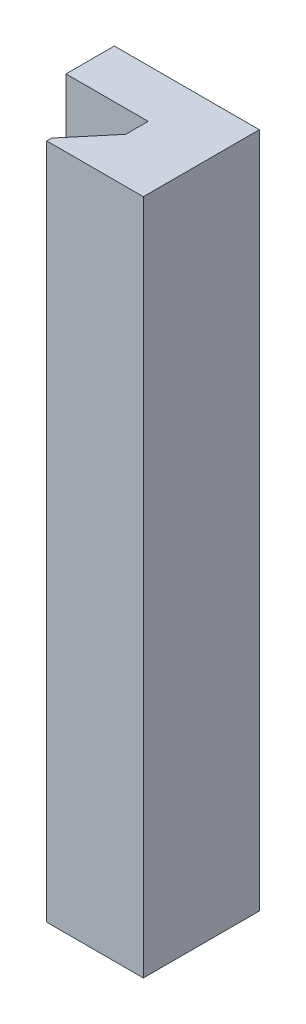
SolidWorks part; units mm, degrees
ref_plane "前视基准面" through (0, 0, 0) normal (0, 0, 1) x (1, 0, 0)
ref_plane "上视基准面" through (0, 0, 0) normal (0, 1, 0) x (1, 0, 0)
ref_plane "右视基准面" through (0, 0, 0) normal (1, 0, 0) x (0, 0, -1)
other "Configuration Table"
sketch "草图1" plane through (0, 0, 0) normal (0, 0, 1) x (1, 0, 0)
  line L1 (0, 0) -> (35, 0)
  line L2 (0, 0) -> (0, -70)
  line L3 (0, -70) -> (35, -70)
  line L4 (35, 0) -> (35, -70)
  dimension "D1" = 70
  dimension "D2" = 35
extrude "凸台-拉伸1" add sketch "草图1" along normal blind 12
sketch "草图2" plane through (0, -70, 0) normal (0, -1, 0) x (1, 0, 0)
  line L10 (17.5, 0) -> (17.5, 12) construction
  line L11 (0, 0) -> (35, 0) construction
  line L12 (28.5, 7.3289) -> (28.5, 5)
  line L13 (25, 12) -> (25, 11.5)
  line L14 (25, 11.5) -> (28.5, 7.3289)
  line L15 (25, 12) -> (0, 12)
  line L16 (0, 12) -> (0, 5)
  line L17 (0, 12) -> (0, 0) construction
  line L18 (0, 5) -> (28.5, 5)
  line L19 (35, 12) -> (35, 0) construction
  dimension "D1" = 10
  dimension "D2" = 140
  dimension "D3" = 3.5
  dimension "D4" = 7
extrude "切除-拉伸1" cut sketch "草图2" against normal up to next
sketch "草图3" plane through (0, 0, 5) normal (0, 0, 1) x (1, 0, 0)
  line L0 (0, -70) -> (28.5, -70) construction
  line L1 (0, 0) -> (20, 0)
  line L2 (0, 0) -> (0, -70)
  line L3 (0, -70) -> (20, -70)
  line L4 (20, 0) -> (20, -70)
  dimension "D1" = 20
extrude "切除-拉伸2" cut sketch "草图3" against normal through all
